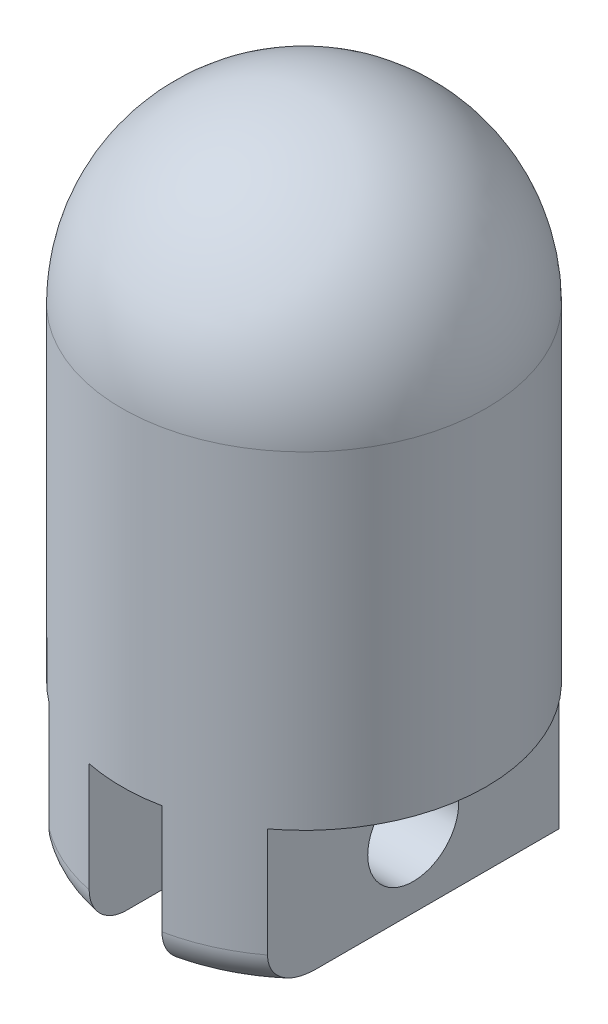
SolidWorks part; units mm, degrees
ref_plane "Front Plane" through (0, 0, 0) normal (0, 0, 1) x (1, 0, 0)
ref_plane "Top Plane" through (0, 0, 0) normal (0, 1, 0) x (1, 0, 0)
ref_plane "Right Plane" through (0, 0, 0) normal (1, 0, 0) x (0, 0, -1)
sketch "Sketch1" plane through (0, 0, 0) normal (0, 0, 1) x (1, 0, 0)
  line L0 (0, 0) -> (0, 5.6026)
  line L1 (0, 0) -> (-12.7, 0)
  line L2 (-12.7, 0) -> (-12.7, 33.02)
  line L6 (0, 5.6026) -> (-2.54, 5.6026)
  line L7 (-2.54, 22.86) -> (-2.54, 5.6026)
  line L8 (0, 43.4927) -> (0, 45.72)
  arc A0 (0, 45.72) -> (-12.7, 33.02) centre (0, 33.02) ccw
  arc A1 (-2.54, 22.86) -> (0, 43.4927) centre (0, 33.02) cw
  dimension "D3" = 25.4
  dimension "D1" = 45.72
  dimension "D2" = 12.7
  dimension "D4" = 2.54
revolve "Revolve1" add sketch "Sketch1" angle 360 about L0
sketch "Sketch2" plane through (0, 0, 0) normal (0, -1, 0) x (1, 0, 0)
  line L0 (-2.54, 12.4434) -> (-2.54, -12.4434)
  line L1 (-7.62, 10.16) -> (-7.62, -10.16)
  line L2 (2.54, 12.4434) -> (2.54, -12.4434)
  line L3 (7.62, 10.16) -> (7.62, -10.16)
  circle A0 centre (0, 0) radius 12.7 construction
  arc A1 (-7.62, 10.16) -> (-7.62, -10.16) centre (0, 0) ccw
  arc A2 (-2.54, -12.4434) -> (2.54, -12.4434) centre (0, 0) ccw
  arc A3 (7.62, -10.16) -> (7.62, 10.16) centre (0, 0) ccw
  arc A4 (2.54, 12.4434) -> (-2.54, 12.4434) centre (0, 0) ccw
  dimension "D1" = 2.54
  dimension "D2" = 5.08
  dimension "D3" = 2.54
  dimension "D4" = 5.08
extrude "Cut-Extrude1" cut sketch "Sketch2" against normal blind 10.16
sketch "Sketch3" plane through (-7.62, 0, 0) normal (-1, 0, 0) x (0, 0, 1)
  line L0 (0, -13.97) -> (0, 13.97) construction
  line L1 (-10.16, 0) -> (10.16, 0) construction
  circle A0 centre (0, 5.08) radius 3.175
  dimension "D2" = 6.35
  dimension "D1" = 5.08
extrude "Cut-Extrude2" cut sketch "Sketch3" against normal through all
fillet "Fillet1" radius 2.54 2 edges at (-5.2067, 0, 11.5836) (5.2067, 0, 11.5836)
